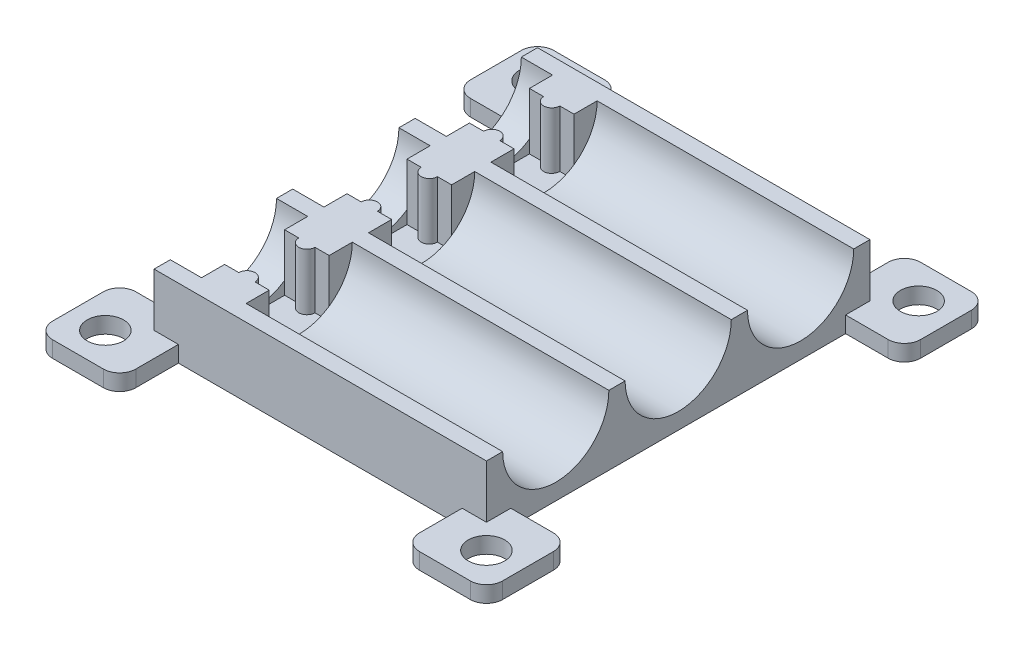
SolidWorks part; units mm, degrees
ref_plane "Front Plane" through (0, 0, 0) normal (0, 0, 1) x (1, 0, 0)
ref_plane "Top Plane" through (0, 0, 0) normal (0, 1, 0) x (1, 0, 0)
ref_plane "Right Plane" through (0, 0, 0) normal (1, 0, 0) x (0, 0, -1)
sketch "Sketch1" plane through (0, 0, 0) normal (1, 0, 0) x (0, 0, -1)
  line L0 (-8.55, 0) -> (-6.55, 0)
  line L1 (-6.55, 0) -> (6.55, 0) construction
  line L2 (6.55, 0) -> (8.55, 0)
  line L3 (-21.65, 0) -> (-8.55, 0) construction
  line L4 (8.55, 0) -> (21.65, 0) construction
  line L5 (-21.65, 0) -> (-23.65, 0)
  line L6 (-23.65, 0) -> (-23.65, -8.55)
  line L7 (-23.65, -8.55) -> (23.65, -8.55)
  line L8 (23.65, -8.55) -> (23.65, 0)
  line L9 (23.65, 0) -> (21.65, 0)
  line L10 (0, -6.55) -> (0, -8.55) construction
  arc A0 (-6.55, 0) -> (6.55, 0) centre (0, 0) ccw
  arc A1 (-21.65, 0) -> (-8.55, 0) centre (-15.1, 0) ccw
  arc A2 (8.55, 0) -> (21.65, 0) centre (15.1, 0) ccw
  dimension "D1" = 13.1
  dimension "D2" = 2
extrude "Boss-Extrude1" add sketch "Sketch1" along normal blind 41
sketch "Sketch2" plane through (0, 0, 0) normal (0, 1, 0) x (1, 0, 0)
  line L0 (6.6, -3.7) -> (6.6, 3.7) construction
  line L1 (5.6, -3.7) -> (5.6, 3.7) construction
  line L2 (0, -7.55) -> (41, -7.55) construction
  line L3 (0, -6.55) -> (0, -8.55) construction
  line L4 (41, -6.55) -> (41, -8.55) construction
  line L5 (0, 7.55) -> (41, 7.55) construction
  line L6 (0, 8.55) -> (0, 6.55) construction
  line L7 (41, 8.55) -> (41, 6.55) construction
  circle A2 centre (6.6, 3.7) radius 1
  circle A3 centre (6.6, -3.7) radius 1
  circle A4 centre (6.6, -11.4) radius 1
  circle A5 centre (6.6, -18.8) radius 1
  circle A6 centre (6.6, 18.8) radius 1
  circle A7 centre (6.6, 11.4) radius 1
  point P4 (6.6, 0)
  point P20 (0, 7.55)
  dimension "D2" = 2
  dimension "D1" = 5.6
  dimension "D3" = 7.4
extrude "Boss-Extrude2" add sketch "Sketch2" against normal up to next
sketch "Sketch4" plane through (0, 0, 0) normal (0, 1, 0) x (1, 0, 0)
  line L0 (41, -6.55) -> (0, -6.55) construction
  line L1 (3.85, -6.55) -> (9.35, -6.55)
  line L2 (3.85, -6.55) -> (3.85, 6.55)
  line L3 (3.85, 6.55) -> (9.35, 6.55)
  line L4 (9.35, -6.55) -> (9.35, 6.55)
  line L5 (41, 6.55) -> (0, 6.55) construction
  line L6 (6.6, -3.7) -> (6.6, 3.7) construction
  line L7 (9.35, 0) -> (3.85, 0) construction
  line L8 (0, -7.55) -> (41, -7.55) construction
  line L9 (0, -6.55) -> (0, -8.55) construction
  line L10 (41, -6.55) -> (41, -8.55) construction
  line L11 (0, 7.55) -> (41, 7.55) construction
  line L12 (0, 8.55) -> (0, 6.55) construction
  line L13 (41, 8.55) -> (41, 6.55) construction
  line L14 (3.85, -21.65) -> (9.35, -21.65)
  line L15 (9.35, -8.55) -> (9.35, -21.65)
  line L16 (3.85, -8.55) -> (9.35, -8.55)
  line L17 (3.85, -8.55) -> (3.85, -21.65)
  line L18 (3.85, 8.55) -> (9.35, 8.55)
  line L19 (9.35, 21.65) -> (9.35, 8.55)
  line L20 (3.85, 21.65) -> (9.35, 21.65)
  line L21 (3.85, 21.65) -> (3.85, 8.55)
  circle A0 centre (6.6, 3.7) radius 1 construction
  circle A1 centre (6.6, -3.7) radius 1 construction
  circle A2 centre (6.6, 3.7) radius 1
  circle A3 centre (6.6, -3.7) radius 1
  circle A4 centre (6.6, -11.4) radius 1
  circle A5 centre (6.6, -18.8) radius 1
  circle A6 centre (6.6, 11.4) radius 1
  circle A7 centre (6.6, 18.8) radius 1
  point P16 (6.6, 0)
  point P17 (6.6, 0)
  dimension "D1" = 5.5
extrude "Cut-Extrude1" cut sketch "Sketch4" against normal blind 7
sketch "Sketch5" plane through (0, -8.55, 0) normal (0, -1, 0) x (1, 0, 0)
  line L0 (0, 23.65) -> (0, 20.65)
  line L1 (-5.2552, 30.9052) -> (1, 30.9052)
  line L2 (-7.2552, 28.9052) -> (-7.2552, 22.65)
  line L3 (-5.2552, 20.65) -> (0, 20.65)
  line L12 (3, 28.9052) -> (3, 23.65)
  line L14 (0, 23.65) -> (3, 23.65)
  line L16 (0, 23.65) -> (-7.2552, 30.9052) construction
  line L17 (-3.0052, 28.9052) -> (-3.0052, 30.9052) construction
  line L18 (-1.4142, 25.0642) -> (0, 23.65) construction
  line L19 (0, 0) -> (41, 0) construction
  line L20 (41, 23.65) -> (41, -23.65) construction
  line L21 (-1.4142, -25.0642) -> (0, -23.65) construction
  line L22 (-3.0052, -28.9052) -> (-3.0052, -30.9052) construction
  line L23 (0, -23.65) -> (-7.2552, -30.9052) construction
  line L24 (0, -23.65) -> (3, -23.65)
  line L25 (3, -28.9052) -> (3, -23.65)
  line L26 (-5.2552, -20.65) -> (0, -20.65)
  line L27 (-7.2552, -28.9052) -> (-7.2552, -22.65)
  line L28 (-5.2552, -30.9052) -> (1, -30.9052)
  line L29 (0, -23.65) -> (0, -20.65)
  line L30 (20.5, 23.65) -> (20.5, -23.65) construction
  line L31 (41, 23.65) -> (0, 23.65) construction
  line L32 (41, -23.65) -> (0, -23.65) construction
  line L33 (41, -23.65) -> (48.2552, -30.9052) construction
  line L34 (44.0052, -28.9052) -> (44.0052, -30.9052) construction
  line L35 (42.4142, -25.0642) -> (41, -23.65) construction
  line L36 (42.4142, 25.0642) -> (41, 23.65) construction
  line L37 (44.0052, 28.9052) -> (44.0052, 30.9052) construction
  line L38 (41, 23.65) -> (48.2552, 30.9052) construction
  line L39 (41, -23.65) -> (41, -20.65)
  line L40 (46.2552, -30.9052) -> (40, -30.9052)
  line L41 (48.2552, -28.9052) -> (48.2552, -22.65)
  line L42 (46.2552, -20.65) -> (41, -20.65)
  line L43 (38, -28.9052) -> (38, -23.65)
  line L44 (41, -23.65) -> (38, -23.65)
  line L45 (41, 23.65) -> (38, 23.65)
  line L46 (38, 28.9052) -> (38, 23.65)
  line L47 (46.2552, 20.65) -> (41, 20.65)
  line L48 (48.2552, 28.9052) -> (48.2552, 22.65)
  line L49 (46.2552, 30.9052) -> (40, 30.9052)
  line L50 (41, 23.65) -> (41, 20.65)
  circle A0 centre (-3.0052, 26.6552) radius 2.25
  arc A1 (-7.2552, 22.65) -> (-5.2552, 20.65) centre (-5.2552, 22.65) ccw
  arc A2 (-5.2552, 30.9052) -> (-7.2552, 28.9052) centre (-5.2552, 28.9052) ccw
  arc A3 (1, 30.9052) -> (3, 28.9052) centre (1, 28.9052) cw
  arc A4 (1, -30.9052) -> (3, -28.9052) centre (1, -28.9052) ccw
  arc A5 (-5.2552, -30.9052) -> (-7.2552, -28.9052) centre (-5.2552, -28.9052) cw
  arc A6 (-7.2552, -22.65) -> (-5.2552, -20.65) centre (-5.2552, -22.65) cw
  circle A7 centre (-3.0052, -26.6552) radius 2.25
  circle A8 centre (44.0052, -26.6552) radius 2.25
  arc A9 (48.2552, -22.65) -> (46.2552, -20.65) centre (46.2552, -22.65) ccw
  arc A10 (46.2552, -30.9052) -> (48.2552, -28.9052) centre (46.2552, -28.9052) ccw
  arc A11 (40, -30.9052) -> (38, -28.9052) centre (40, -28.9052) cw
  arc A12 (40, 30.9052) -> (38, 28.9052) centre (40, 28.9052) ccw
  arc A13 (46.2552, 30.9052) -> (48.2552, 28.9052) centre (46.2552, 28.9052) cw
  arc A14 (48.2552, 22.65) -> (46.2552, 20.65) centre (46.2552, 22.65) cw
  circle A15 centre (44.0052, 26.6552) radius 2.25
  dimension "D1" = 4.5
  dimension "D4" = 2
  dimension "D5" = 2
  dimension "D2" = 3
  dimension "D3" = 2
extrude "Boss-Extrude3" add sketch "Sketch5" against normal blind 2
sketch "Sketch6" plane through (0, 0, 0) normal (0, 1, 0) x (1, 0, 0)
  line L0 (0, 0) -> (41, 0) construction
  line L1 (3.85, -3.7) -> (9.35, -3.7)
  line L2 (9.35, -3.7) -> (9.35, -6.55)
  line L3 (9.35, -6.55) -> (3.85, -6.55)
  line L4 (3.85, -6.55) -> (3.85, -3.7)
  line L5 (7.6, -3.7) -> (5.6, -3.7) construction
  line L6 (7.6, 3.7) -> (5.6, 3.7) construction
  line L7 (3.85, 6.55) -> (3.85, 3.7)
  line L8 (9.35, 6.55) -> (3.85, 6.55)
  line L9 (9.35, 3.7) -> (9.35, 6.55)
  line L10 (3.85, 3.7) -> (9.35, 3.7)
  line L11 (0, -7.55) -> (41, -7.55) construction
  line L12 (0, 7.55) -> (41, 7.55) construction
  line L13 (0, -6.55) -> (0, -8.55) construction
  line L14 (0, 8.55) -> (0, 6.55) construction
  line L15 (41, 8.55) -> (41, 6.55) construction
  line L16 (41, -6.55) -> (41, 6.55) construction
  line L17 (41, -6.55) -> (41, -8.55) construction
  line L18 (9.35, -6.55) -> (9.35, 6.55) construction
  line L19 (5.6, -3.7) -> (7.6, -3.7) construction
  line L20 (5.6, -11.4) -> (7.6, -11.4) construction
  line L21 (7.6, -18.8) -> (5.6, -18.8) construction
  line L22 (7.6, -11.4) -> (5.6, -11.4) construction
  line L23 (3.85, -18.8) -> (9.35, -18.8)
  line L24 (9.35, -18.8) -> (9.35, -21.65)
  line L25 (9.35, -21.65) -> (3.85, -21.65)
  line L26 (3.85, -21.65) -> (3.85, -18.8)
  line L27 (3.85, -8.55) -> (3.85, -11.4)
  line L28 (9.35, -8.55) -> (3.85, -8.55)
  line L29 (9.35, -11.4) -> (9.35, -8.55)
  line L30 (3.85, -11.4) -> (9.35, -11.4)
  line L31 (5.6, 18.8) -> (7.6, 18.8) construction
  line L32 (7.6, 11.4) -> (5.6, 11.4) construction
  line L33 (7.6, 18.8) -> (5.6, 18.8) construction
  line L34 (3.85, 11.4) -> (9.35, 11.4)
  line L35 (9.35, 11.4) -> (9.35, 8.55)
  line L36 (9.35, 8.55) -> (3.85, 8.55)
  line L37 (3.85, 8.55) -> (3.85, 11.4)
  line L38 (3.85, 21.65) -> (3.85, 18.8)
  line L39 (9.35, 21.65) -> (3.85, 21.65)
  line L40 (9.35, 18.8) -> (9.35, 21.65)
  line L41 (3.85, 18.8) -> (9.35, 18.8)
  circle A0 centre (6.6, -3.7) radius 1 construction
  circle A1 centre (6.6, -3.7) radius 1 construction
  point P18 (0, 0)
extrude "Boss-Extrude4" add sketch "Sketch6" against normal up to surface (7 mm away) up to face at (6.6, -7, -19.8)
